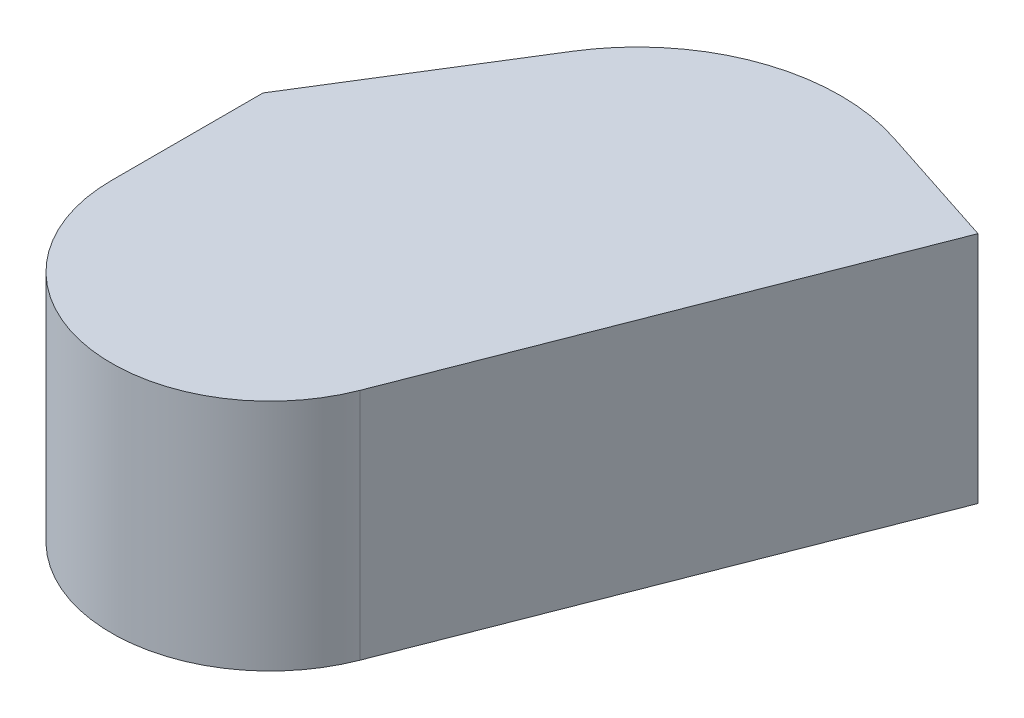
SolidWorks part; units mm, degrees
material "PBT General Purpose"
ref_plane "Front Plane" through (0, 0, 0) normal (0, 0, 1) x (1, 0, 0)
ref_plane "Top Plane" through (0, 0, 0) normal (0, 1, 0) x (1, 0, 0)
ref_plane "Right Plane" through (0, 0, 0) normal (1, 0, 0) x (0, 0, -1)
sketch "Sketch1" plane through (0, 0, 0) normal (0, 1, 0) x (1, 0, 0)
  line L0 (-66.6738, 0) -> (-37.0678, 47.6333)
  line L1 (0, 0) -> (-66.6738, 0) construction
  line L2 (0, 0) -> (0, -77.4519) construction
  line L3 (0, -77.4519) -> (-66.6738, -77.4519)
  line L4 (-66.6738, 0) -> (-66.6738, -77.4519)
  line L5 (21.8265, 69.1139) -> (53.1385, 58.9035)
  line L6 (53.1385, 58.9035) -> (0, -77.4519)
  arc A0 (-37.0678, 47.6333) -> (21.8265, 69.1139) centre (6.0775, 20.8169) cw
  dimension "D1" = 50.8
extrude "Boss-Extrude1" add sketch "Sketch1" along normal blind 58.42
fillet "Fillet3" radius 39.6032 4 edges at (0, 29.21, 77.4519) (-66.6738, 29.21, 77.4519) (-33.3369, 58.42, 77.4519) (-33.3369, 0, 77.4519)
